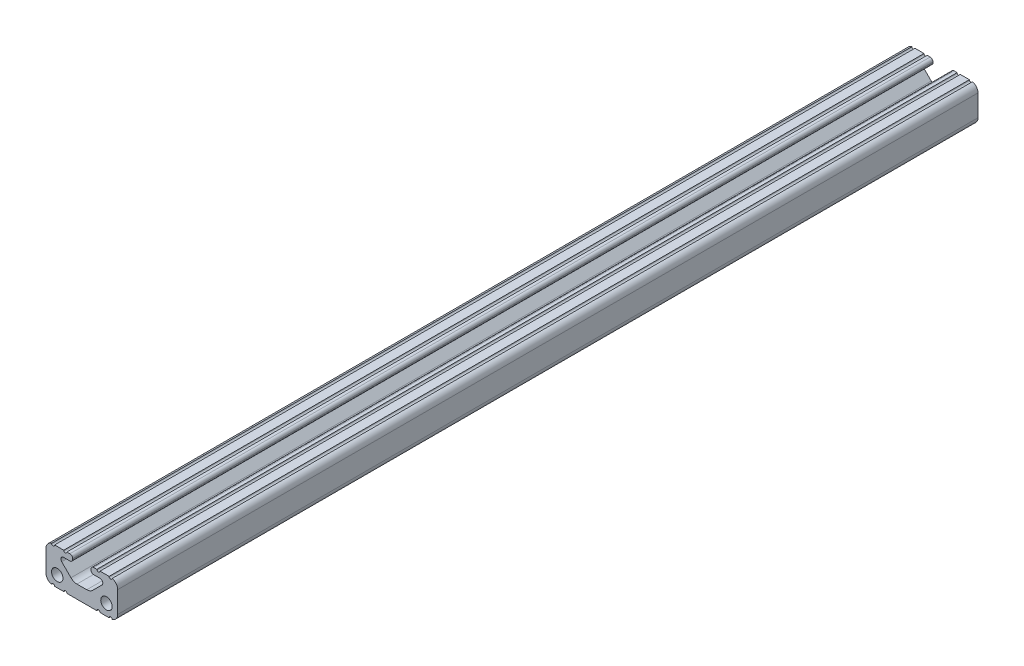
SolidWorks part; units mm, degrees
ref_plane "Front Plane" through (0, 0, 0) normal (0, 0, 1) x (1, 0, 0)
ref_plane "Top Plane" through (0, 0, 0) normal (0, 1, 0) x (1, 0, 0)
ref_plane "Right Plane" through (0, 0, 0) normal (1, 0, 0) x (0, 0, -1)
sketch "Sketch1" plane through (0, 0, 0) normal (0, 0, 1) x (1, 0, 0)
  line L0 (0, 6.35) -> (0, -6.35) construction
  line L1 (0, -6.35) -> (12.7, -6.35)
  line L2 (12.7, -6.35) -> (12.7, 6.35)
  line L3 (12.7, 6.35) -> (3.2512, 6.35)
  line L4 (3.2512, 6.35) -> (3.2512, 4.1402)
  line L5 (3.2512, 4.1402) -> (6.4224, 4.1402)
  line L6 (7.1255, 2.4426) -> (2.9811, -1.7018)
  line L7 (2.9811, -1.7018) -> (0, -1.7018)
  circle A0 centre (8.7249, -2.3876) radius 2.032
  arc A1 (6.4224, 4.1402) -> (7.1255, 2.4426) centre (6.4224, 3.1458) cw
  dimension "Center Hole Diameter" = 4.064
  dimension "D3" = 0.9944
  dimension "Rail Height" = 25.4
  dimension "Rail Width" = 12.7
  dimension "Hole CtoC" = 17.4498
  dimension "D1" = 3.9624
  dimension "T-Slot Width" = 6.5024
  dimension "Thickness" = 2.2098
  dimension "Inner Slot Width" = 14.8336
  dimension "Slot Depth" = 5.842
  dimension "D2" = 45
sketch "Sketch2" plane through (0, 0, 0) normal (1, 0, 0) x (0, 0, -1)
  line L0 (-152.4, -6.35) -> (152.4, -6.35) construction
  line L1 (-127, 0) -> (127, 0) construction
  dimension "Length" = 304.8
  dimension "D1" = 25.4
sketch "Sketch3" plane through (0, 0, 0) normal (0, 0, 1) x (1, 0, 0)
  line L0 (3.2512, 6.35) -> (3.2512, 4.1402) construction
  line L1 (12.7, 6.35) -> (3.2512, 6.35) construction
  line L2 (3.2512, 4.1402) -> (6.4224, 4.1402) construction
  line L3 (3.2512, 5.3556) -> (3.2512, 5.1346)
  line L4 (12.7, -6.35) -> (12.7, 6.35) construction
  line L5 (0, -6.35) -> (12.7, -6.35) construction
  line L6 (2.9811, -1.7018) -> (0, -1.7018) construction
  line L7 (7.1255, 2.4426) -> (2.9811, -1.7018) construction
  line L8 (0, -1.7018) -> (1.7454, -1.7018)
  line L9 (4.2456, 4.1402) -> (6.4224, 4.1402)
  line L10 (3.8549, -0.828) -> (7.1255, 2.4426)
  line L11 (0, -1.7018) -> (0, -6.35)
  line L12 (0, -6.35) -> (10.16, -6.35)
  line L13 (12.7, -3.81) -> (12.7, 3.81)
  line L14 (4.2456, 6.35) -> (10.16, 6.35)
  arc A0 (3.2512, 5.3556) -> (4.2456, 6.35) centre (4.2456, 5.3556) cw
  arc A1 (3.2512, 5.1346) -> (4.2456, 4.1402) centre (4.2456, 5.1346) ccw
  arc A2 (7.1255, 2.4426) -> (6.4224, 4.1402) centre (6.4224, 3.1458) ccw construction
  arc A3 (10.16, 6.35) -> (12.7, 3.81) centre (10.16, 3.81) cw
  arc A4 (10.16, -6.35) -> (12.7, -3.81) centre (10.16, -3.81) ccw
  arc A5 (7.1255, 2.4426) -> (6.4224, 4.1402) centre (6.4224, 3.1458) ccw
  circle A6 centre (8.7249, -2.3876) radius 2.032 construction
  circle A7 centre (8.7249, -2.3876) radius 2.032
  arc A8 (1.7454, -1.7018) -> (3.8549, -0.828) centre (1.7454, 1.2814) ccw
  dimension "D2" = 2.9832
  dimension "D1" = 2.54
extrude "Boss-Extrude1" add sketch "Sketch3" along normal mid plane 304.8
sketch "Sketch4" plane through (0, 0, 0) normal (0, 0, 1) x (1, 0, 0)
  line L0 (12.7, 6.35) -> (3.2512, 6.35) construction
  line L1 (0, -6.35) -> (12.7, -6.35) construction
  line L2 (10.7569, -2.3876) -> (10.7569, 6.35) construction
  line L3 (6.4224, 3.1458) -> (6.4224, 6.35) construction
  circle A0 centre (5.8699, 6.35) radius 0.5524
  circle A1 centre (10.2045, 6.35) radius 0.5524
  circle A2 centre (5.8699, -6.35) radius 0.5524
  circle A3 centre (10.2045, -6.35) radius 0.5524
  circle A4 centre (8.7249, -2.3876) radius 2.032 construction
  dimension "D1" = 1.1049
extrude "Cut-Extrude1" cut sketch "Sketch4" against normal through all both and the other way through all
mirror "Mirror1" about plane through (0, 0, 0) normal (1, 0, 0) of bodies 135
equation "\"D3@Sketch1\"=\"Thickness@Sketch1\"*0.45"
equation "\"D1@Sketch3\"=\"Rail Width@Sketch1\"*0.2"
equation "\"D2@Sketch3\"=\"D3@Sketch1\"*3"
equation "\"D1@Boss-Extrude1\"=\"length@sketch2\""
equation "\"D1@Sketch4\"=\"Thickness@Sketch1\"*0.5"
